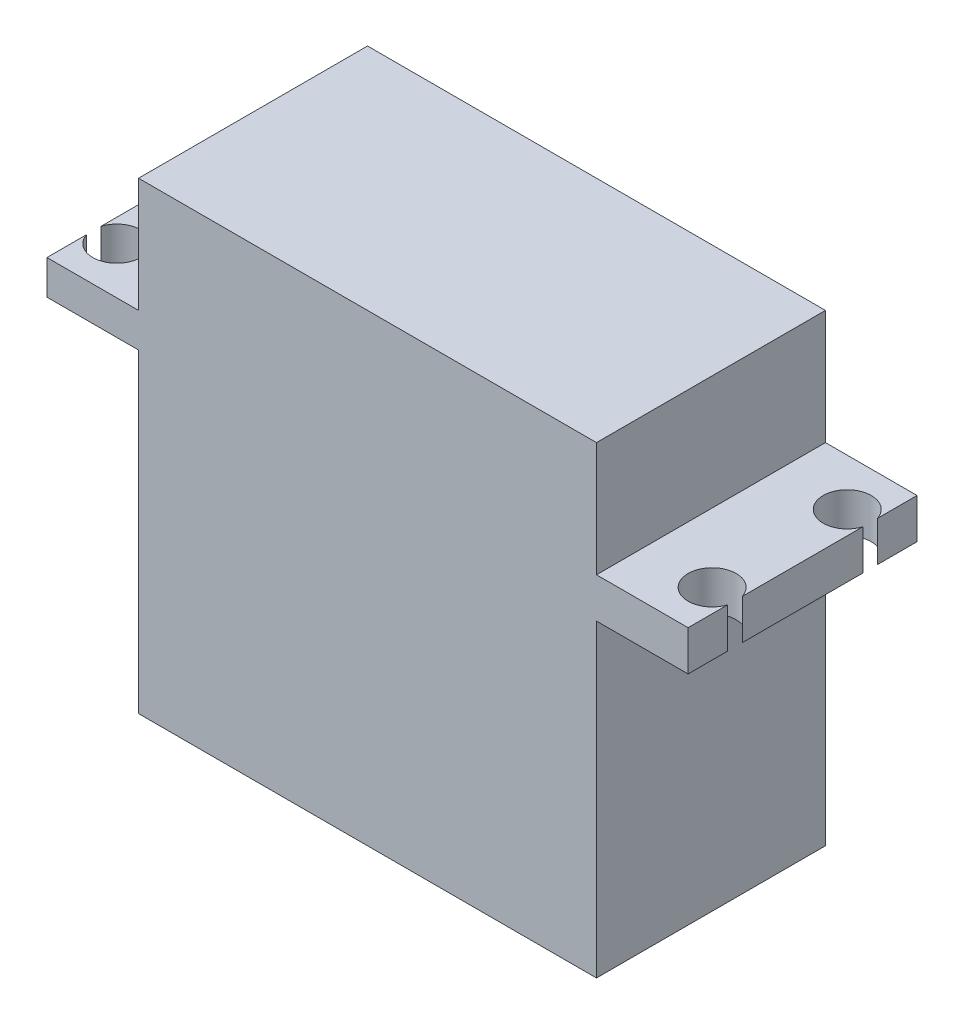
SolidWorks part; units mm, degrees
ref_plane "Front Plane" through (0, 0, 0) normal (0, 0, 1) x (1, 0, 0)
ref_plane "Top Plane" through (0, 0, 0) normal (0, 1, 0) x (1, 0, 0)
ref_plane "Right Plane" through (0, 0, 0) normal (1, 0, 0) x (0, 0, -1)
sketch "Sketch2" plane through (0, 0, 0) normal (0, 0, 1) x (1, 0, 0)
  line L0 (0, 0) -> (0, 40.5)
  line L1 (0, 40.5) -> (40, 40.5)
  line L2 (40, 40.5) -> (40, 0)
  line L3 (40, 0) -> (0, 0)
  dimension "D1" = 40.5
  dimension "D2" = 40
extrude "Boss-Extrude1" add sketch "Sketch2" against normal blind 20
sketch "Sketch3" plane through (40, 0, 0) normal (1, 0, 0) x (0, 0, -1)
  line L0 (0, 30.5) -> (20, 30.5)
  line L1 (0, 0) -> (0, 40.5) construction
  line L2 (20, 0) -> (20, 40.5) construction
  line L3 (0, 27) -> (20, 27)
  line L4 (0, 27) -> (0, 30.5)
  line L5 (20, 30.5) -> (20, 27)
  dimension "D1" = 10
  dimension "D2" = 27
extrude "Boss-Extrude2" add sketch "Sketch3" along normal blind 8
sketch "Sketch4" plane through (0, 30.5, 0) normal (0, 1, 0) x (1, 0, 0)
  line L0 (48, 20) -> (40, 20) construction
  line L1 (40, 20) -> (40, 0) construction
  line L2 (-952, 10) -> (49048, 10) construction
  line L3 (48, 20) -> (48, 0) construction
  circle A0 centre (46, 15.9) radius 2.1
  circle A1 centre (46, 4.1) radius 2.1
  point P11 (48, 10)
  dimension "D1" = 4.2
  dimension "D2" = 4.1
  dimension "D3" = 6
extrude "Cut-Extrude1" cut sketch "Sketch4" against normal blind 8
sketch "Sketch5" plane through (0, 0, 0) normal (-1, 0, 0) x (0, 0, 1)
  line L0 (-20, 27.5) -> (-20, 30.5)
  line L1 (-20, 40.5) -> (-20, 0) construction
  line L2 (-20, 30.5) -> (0, 30.5)
  line L3 (0, 40.5) -> (0, 0) construction
  line L4 (0, 30.5) -> (0, 27.5)
  line L5 (0, 27.5) -> (-20, 27.5)
  line L6 (-20, 40.5) -> (0, 40.5) construction
  dimension "D1" = 3
  dimension "D2" = 10
extrude "Boss-Extrude3" add sketch "Sketch5" along normal blind 8
sketch "Sketch6" plane through (0, 30.5, 0) normal (0, 1, 0) x (1, 0, 0)
  line L0 (0, 0) -> (0, 20) construction
  line L1 (-8, 20) -> (0, 20) construction
  line L2 (-1008, 10) -> (48992, 10) construction
  line L3 (-8, 0) -> (-8, 20) construction
  circle A0 centre (-6, 15.9) radius 2.1
  circle A1 centre (-6, 4.1) radius 2.1
  point P11 (-8, 10)
  dimension "D1" = 4.2
  dimension "D2" = 6
  dimension "D3" = 4.1
extrude "Cut-Extrude2" cut sketch "Sketch6" against normal blind 8
